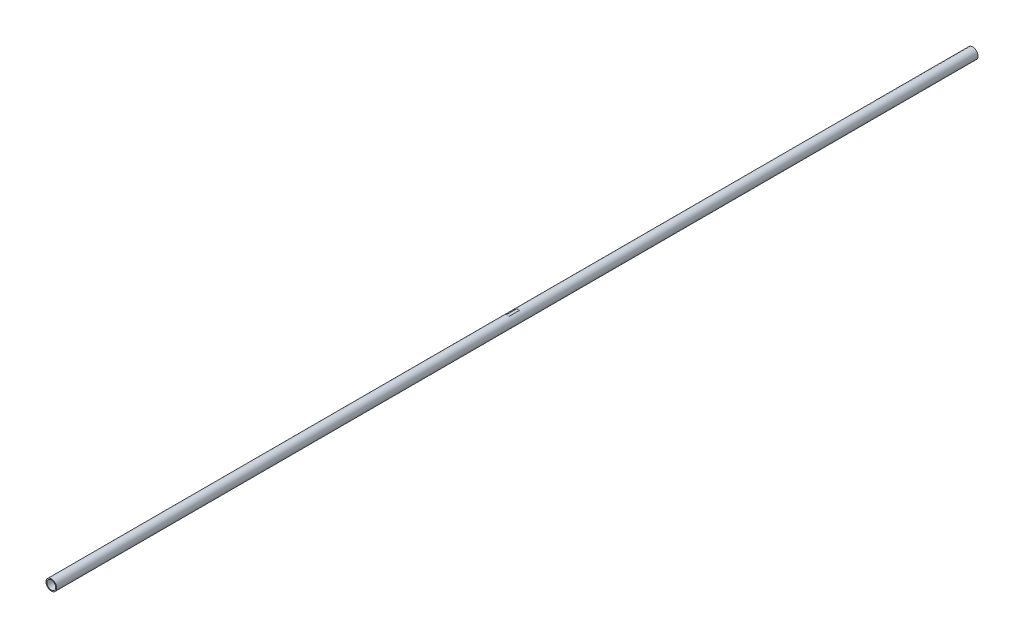
SolidWorks part; units mm, degrees
material "Plain Carbon Steel"
ref_plane "Front Plane" through (0, 0, 0) normal (0, 0, 1) x (1, 0, 0)
ref_plane "Top Plane" through (0, 0, 0) normal (0, 1, 0) x (1, 0, 0)
ref_plane "Right Plane" through (0, 0, 0) normal (1, 0, 0) x (0, 0, -1)
sketch "Sketch1" plane through (0, 0, 0) normal (0, 0, 1) x (1, 0, 0)
  circle A0 centre (0, 0) radius 21.082
  circle A1 centre (0, 0) radius 17.526
  dimension "D1" = 42.164
  dimension "D2" = 3.556
extrude "Boss-Extrude1" add sketch "Sketch1" along normal blind 3657.6
sketch "Sketch4" plane through (0, 0, 0) normal (1, 0, 0) x (0, 0, -1)
  line L1 (-1846.1636, 26.1051) -> (-1804.5158, 26.1051)
  line L2 (-1846.1636, 26.1051) -> (-1846.1636, 20.3321)
  line L3 (-1846.1636, 20.3321) -> (-1804.5158, 20.3321)
  line L4 (-1804.5158, 26.1051) -> (-1804.5158, 20.3321)
extrude "Cut-Extrude1" cut sketch "Sketch4" against normal through all both and the other way through all
